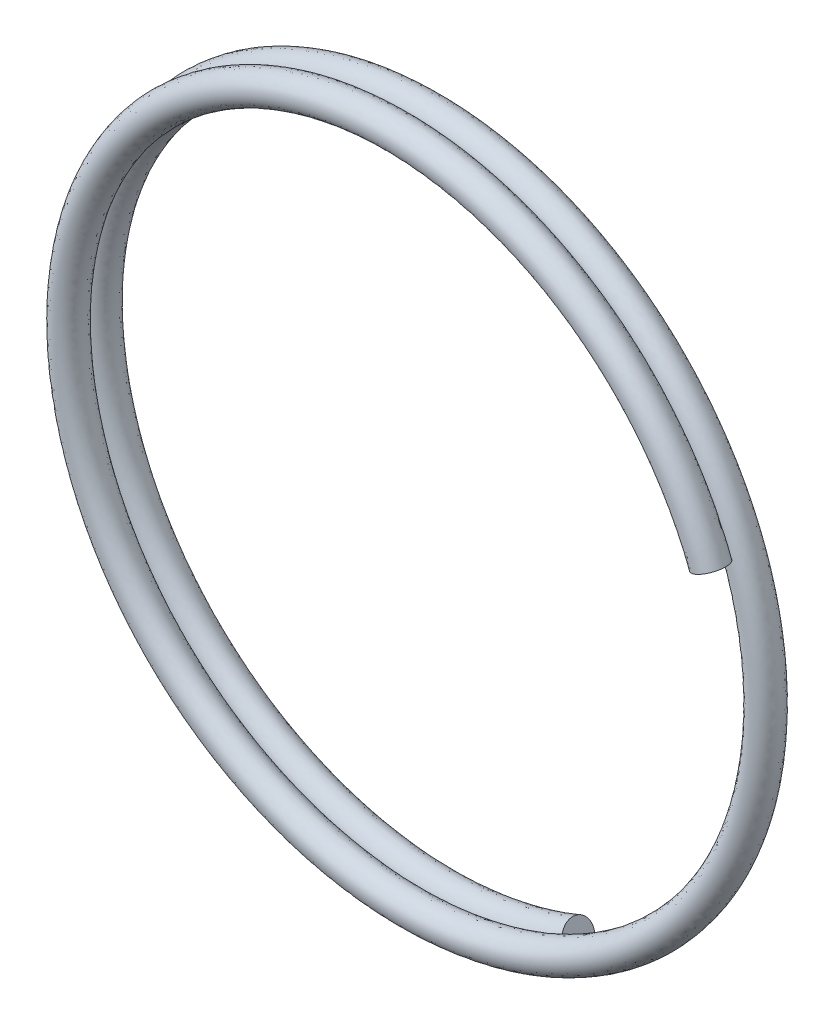
SolidWorks part; units mm, degrees
ref_plane "Front Plane" through (0, 0, 0) normal (0, 0, 1) x (1, 0, 0)
ref_plane "Top Plane" through (0, 0, 0) normal (0, 1, 0) x (1, 0, 0)
ref_plane "Right Plane" through (0, 0, 0) normal (1, 0, 0) x (0, 0, -1)
sketch "Sketch1" plane through (0, 0, 0) normal (0, 0, 1) x (1, 0, 0)
  circle A0 centre (0, 0) radius 11
  dimension "D1" = 22
curve "Helix/Spiral1" pitch 1.0286 height 1.8 turns 1.75
ref_plane "Plane1" through (4.1207, -10.199, -1.8) normal (0.9271, 0.3746, -0.0149) x (-0.3738, 0.9267, 0.0398)
sketch "Sketch2" plane through (4.1207, -10.199, -1.8) normal (0.9271, 0.3746, -0.0149) x (-0.3738, 0.9267, 0.0398)
  circle A0 centre (0.0147, -0.0071) radius 0.5
  dimension "D1" = 1
sweep "Sweep1" add profiles "Sketch2" path "Helix/Spiral1"
